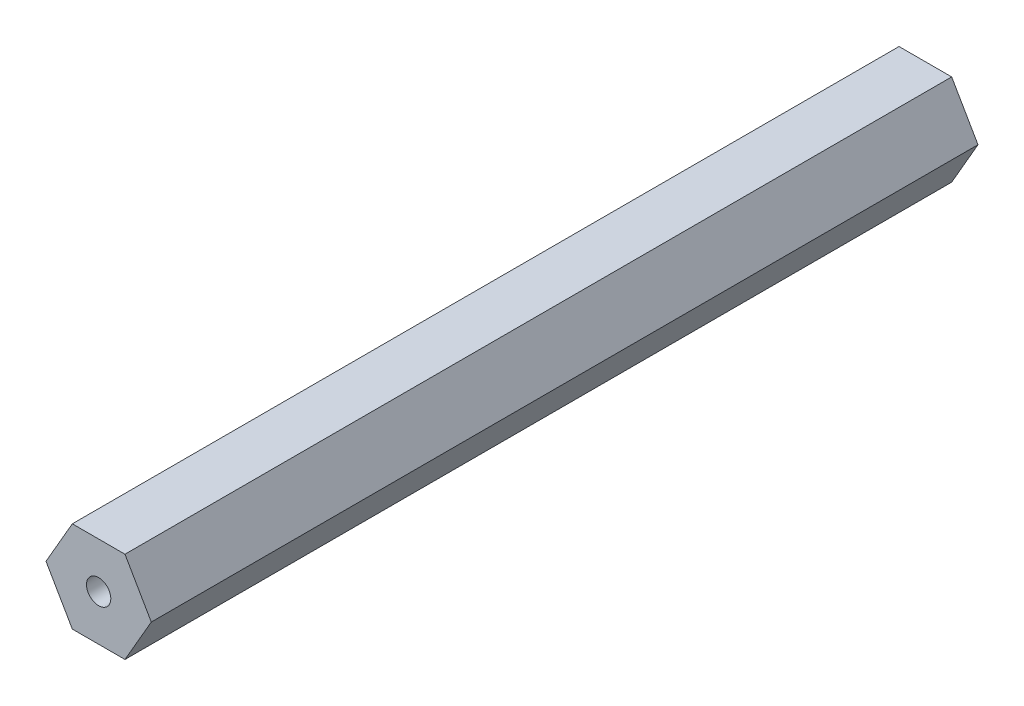
SolidWorks part; units mm, degrees
ref_plane "Front Plane" through (0, 0, 0) normal (0, 0, 1) x (1, 0, 0)
ref_plane "Top Plane" through (0, 0, 0) normal (0, 1, 0) x (1, 0, 0)
ref_plane "Right Plane" through (0, 0, 0) normal (1, 0, 0) x (0, 0, -1)
sketch "Sketch1" plane through (0, 0, 0) normal (0, 0, 1) x (1, 0, 0)
  line L1 (16.408, -2.6676) -> (13.6584, 2.0949)
  line L2 (13.6584, 2.0949) -> (8.1591, 2.0949)
  line L3 (8.1591, 2.0949) -> (5.4095, -2.6676)
  line L4 (5.4095, -2.6676) -> (8.1591, -7.4301)
  line L5 (8.1591, -7.4301) -> (13.6584, -7.4301)
  line L6 (13.6584, -7.4301) -> (16.408, -2.6676)
  circle A0 centre (10.9088, -2.6676) radius 4.7625 construction
  circle A1 centre (10.9088, -2.6676) radius 1.27
  dimension "D1" = 9.525
extrude "Boss-Extrude1" add sketch "Sketch1" along normal blind 86.36
